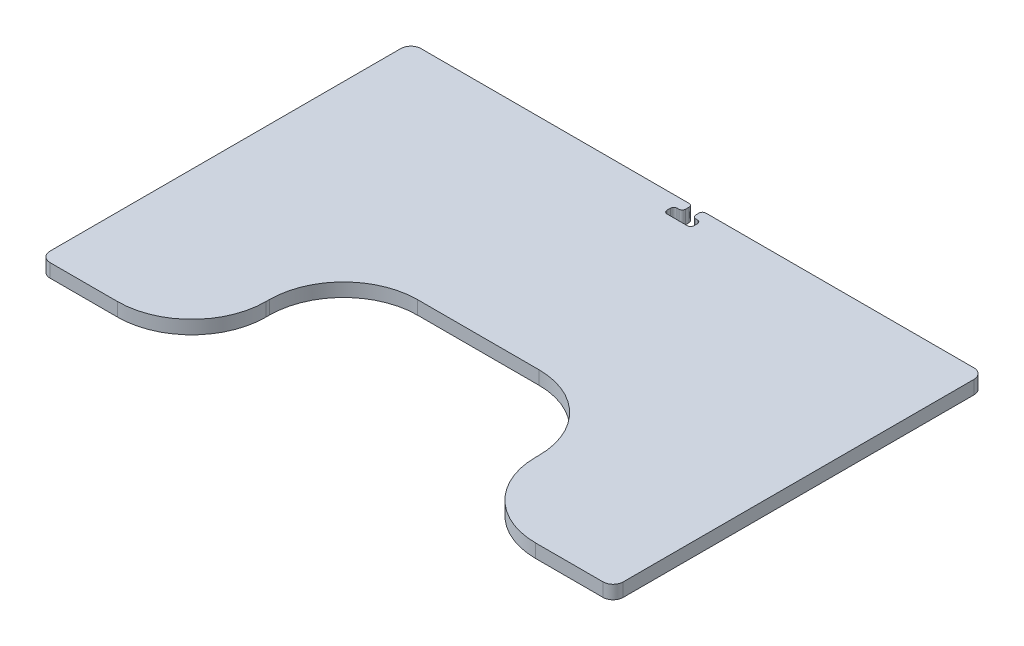
SolidWorks part; units mm, degrees
material "Pine"
ref_plane "Front Plane" through (0, 0, 0) normal (0, 0, 1) x (1, 0, 0)
ref_plane "Top Plane" through (0, 0, 0) normal (0, 1, 0) x (1, 0, 0)
ref_plane "Right Plane" through (0, 0, 0) normal (1, 0, 0) x (0, 0, -1)
sketch "Sketch1" plane through (0, 0, 0) normal (0, 1, 0) x (1, 0, 0)
  line L0 (0, 0) -> (0, 1100) construction
  line L1 (850, 1100) -> (-850, 1100)
  line L2 (-850, 1100) -> (-850, 0)
  line L3 (-850, 0) -> (-400, 0)
  line L4 (-400, 0) -> (-400, 450)
  line L5 (-400, 450) -> (400, 450)
  line L6 (400, 0) -> (400, 450)
  line L7 (850, 0) -> (400, 0)
  line L8 (850, 1100) -> (850, 0)
  point P9 (0, 450)
  dimension "D1" = 1100
  dimension "D2" = 1700
  dimension "D3" = 800
  dimension "D4" = 450
extrude "Boss-Extrude1" add sketch "Sketch1" along normal blind 40
fillet "Fillet1" radius 220 4 edges at (-400, 20, 0) (-400, 20, -450) (400, 20, 0) (400, 20, -450)
fillet "Fillet2" radius 30 4 edges at (850, 20, 0) (-850, 20, 0) (-850, 20, -1100) (850, 20, -1100)
sketch "Sketch2" plane through (0, 40, 0) normal (0, 1, 0) x (1, 0, 0)
  line L0 (-15, 1100) -> (-15, 1070)
  line L2 (-15, 1070) -> (-40, 1070)
  line L3 (-40, 1070) -> (-40, 1040)
  line L4 (-40, 1040) -> (40, 1040)
  line L5 (0, 1040) -> (0, 1100) construction
  line L6 (40, 1070) -> (40, 1040)
  line L7 (15, 1070) -> (40, 1070)
  line L8 (15, 1100) -> (15, 1070)
  line L9 (820, 1100) -> (-820, 1100) construction
  dimension "D1" = 30
  dimension "D2" = 30
  dimension "D3" = 80
  dimension "D4" = 30
extrude "Cut-Extrude1" cut sketch "Sketch2" against normal through all and the other way through all flip side to cut
fillet "Fillet3" radius 10 8 edges at (15, 20, -1100) (15, 20, -1070) (40, 20, -1070) (40, 20, -1040) (-40, 20, -1040) (-40, 20, -1070) (-15, 20, -1070) (-15, 20, -1100)
